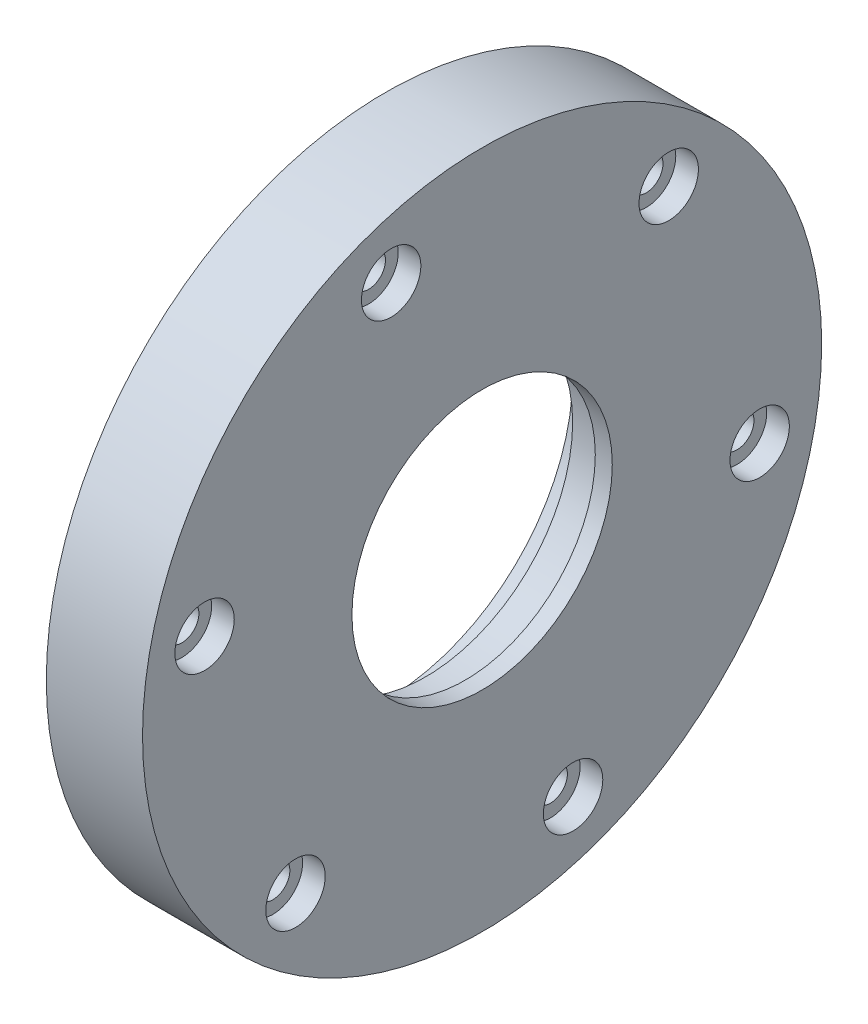
SolidWorks part; units mm, degrees
ref_plane "Front Plane" through (0, 0, 0) normal (0, 0, 1) x (1, 0, 0)
ref_plane "Top Plane" through (0, 0, 0) normal (0, 1, 0) x (1, 0, 0)
ref_plane "Right Plane" through (0, 0, 0) normal (1, 0, 0) x (0, 0, -1)
sketch "Sketch1" plane through (0, 0, 0) normal (0, 0, 1) x (1, 0, 0)
  line L0 (0, 0) -> (14, 0) construction
  line L1 (0, 60) -> (0, 33)
  line L2 (0, 33) -> (7, 33)
  line L3 (7, 33) -> (7, 26)
  line L4 (7, 26) -> (14, 26)
  line L5 (14, 26) -> (14, 23)
  line L6 (14, 23) -> (17, 23)
  line L7 (17, 23) -> (17, 60)
  line L8 (17, 60) -> (0, 60)
  dimension "D1" = 17
  dimension "D2" = 26
  dimension "D3" = 7
  dimension "D4" = 3
  dimension "D5" = 60
  dimension "D6" = 33
  dimension "D7" = 3
revolve "Revolve1" add sketch "Sketch1" angle 360 about L0
sketch "Sketch2" plane through (0, 0, 0) normal (-1, 0, 0) x (0, 0, 1)
  circle A0 centre (0, 0) radius 40 construction
  circle A1 centre (0, 40) radius 2.5
  circle A2 centre (15.3073, 36.9552) radius 2.5
  circle A3 centre (28.2843, 28.2843) radius 2.5
  circle A4 centre (36.9552, 15.3073) radius 2.5
  circle A5 centre (40, 0) radius 2.5
  circle A6 centre (36.9552, -15.3073) radius 2.5
  circle A7 centre (28.2843, -28.2843) radius 2.5
  circle A8 centre (15.3073, -36.9552) radius 2.5
  circle A9 centre (0, -40) radius 2.5
  circle A10 centre (-15.3073, -36.9552) radius 2.5
  circle A11 centre (-28.2843, -28.2843) radius 2.5
  circle A12 centre (-36.9552, -15.3073) radius 2.5
  circle A13 centre (-40, 0) radius 2.5
  circle A14 centre (-36.9552, 15.3073) radius 2.5
  circle A15 centre (-28.2843, 28.2843) radius 2.5
  circle A16 centre (-15.3073, 36.9552) radius 2.5
  point P37 (0, 0)
  dimension "D1" = 80
  dimension "D2" = 5
  dimension "D3" = 16
extrude "Cut-Extrude1" cut sketch "Sketch2" against normal blind 4
sketch "Sketch3" plane through (17, 0, 0) normal (1, 0, 0) x (0, 0, -1)
  circle A0 centre (49.0393, -9.7545) radius 3
  circle A1 centre (16.072, -47.3465) radius 3
  circle A2 centre (-32.9673, -37.592) radius 3
  circle A3 centre (-49.0393, 9.7545) radius 3
  circle A4 centre (-16.072, 47.3465) radius 3
  circle A5 centre (32.9673, 37.592) radius 3
  point P20 (0, 0)
  dimension "D2" = 6
  dimension "D1" = 6
extrude "Cut-Extrude4" cut sketch "Sketch3" against normal through all
sketch "Sketch4" plane through (17, 0, 0) normal (1, 0, 0) x (0, 0, -1)
  circle A0 centre (32.9673, 37.592) radius 5.25
  circle A1 centre (49.0393, -9.7545) radius 5.25
  circle A2 centre (16.072, -47.3465) radius 5.25
  circle A3 centre (-32.9673, -37.592) radius 5.25
  circle A4 centre (-49.0393, 9.7545) radius 5.25
  circle A5 centre (-16.072, 47.3465) radius 5.25
  point P20 (0, 0)
  dimension "D1" = 10.5
  dimension "D2" = 6
extrude "Cut-Extrude5" cut sketch "Sketch4" against normal blind 4
sketch "Sketch5" [suppressed] plane through (17, 0, 0) normal (1, 0, 0) x (0, 0, -1)
  line L0 (32.9673, 37.592) -> (0, 0) construction
  line L1 (0, 0) -> (41.6649, 14.1433) construction
  circle A0 centre (32.9673, 37.592) radius 3.3
  circle A1 centre (49.0393, -9.7545) radius 3.3
  circle A2 centre (16.072, -47.3465) radius 3.3
  circle A3 centre (-32.9673, -37.592) radius 3.3
  circle A4 centre (-49.0393, 9.7545) radius 3.3
  circle A5 centre (-16.072, 47.3465) radius 3.3
  circle A8 centre (0, 0) radius 44 construction
  circle A9 centre (41.6649, 14.1433) radius 3.3
  circle A10 centre (-8.584, -43.1546) radius 3.3
  circle A11 centre (-33.081, 29.0112) radius 3.3
  point P19 (0, 0)
  point P33 (0, 0)
  dimension "D1" = 6.6
  dimension "D4" = 88
  dimension "D5" = 30
  dimension "D2" = 6
  dimension "D3" = 3
extrude "Cut-Extrude6" [suppressed] cut sketch "Sketch5" against normal blind 10
chamfer "Chamfer1" [suppressed] distance 1 angle 45
equation "\"R_ROLL\"= 5mm"
equation "\"D_SUN\"= 80mm"
equation "\"NUM_ROLL\"= 16"
equation "\"RHO\"= 1mm"
equation "\"D_SHAFT\"= 15mm"
equation "\"D_OUTPUT\"= 40mm"
equation "\"NUM_OUT\"= 6"
equation "\"R_OUT_ROLL\"= 5mm"
equation "\"D1@Sketch2\"=\"D_SUN\""
equation "\"D3@Sketch2\"=\"NUM_ROLL\""
